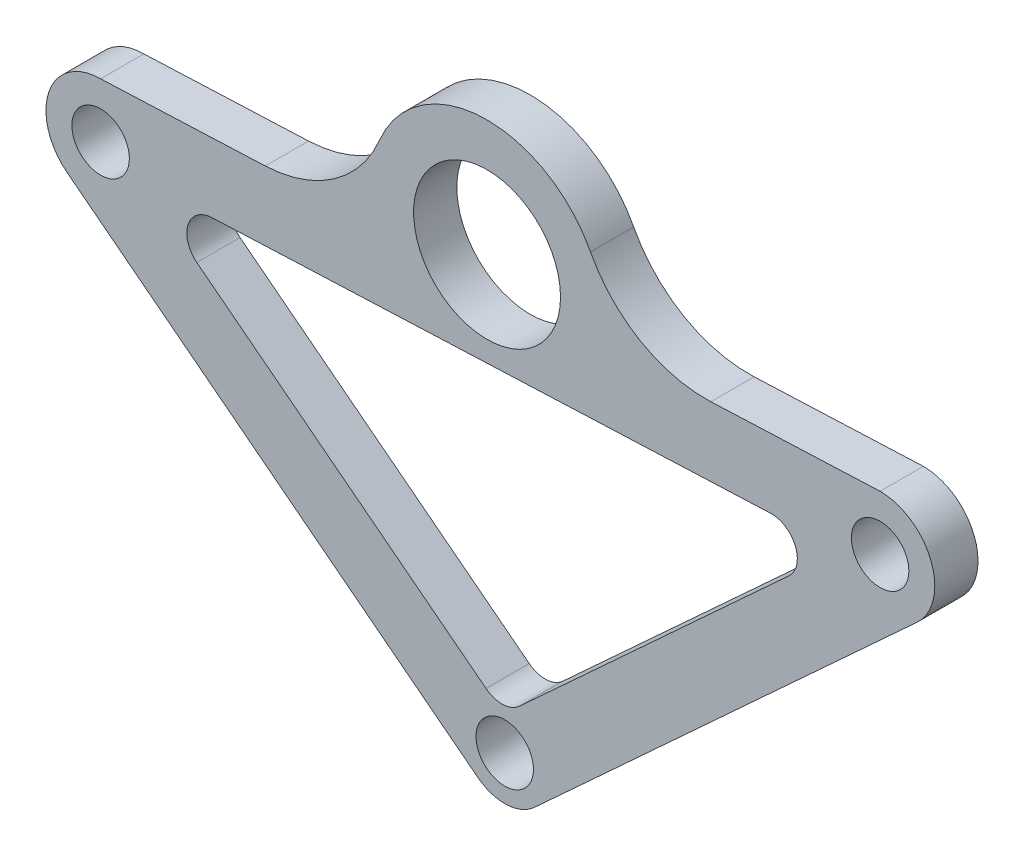
SolidWorks part; units mm, degrees
ref_plane "Front Plane" through (0, 0, 0) normal (0, 0, 1) x (1, 0, 0)
ref_plane "Top Plane" through (0, 0, 0) normal (0, 1, 0) x (1, 0, 0)
ref_plane "Right Plane" through (0, 0, 0) normal (1, 0, 0) x (0, 0, -1)
sketch "Sketch1" plane through (0, 0, 0) normal (0, 0, 1) x (1, 0, 0)
  line L0 (57.5247, 15.0168) -> (37.9425, 14.1987)
  line L1 (44.8204, 6.4791) -> (-19.8121, 3.7789)
  line L2 (-21.5254, -1.5891) -> (11.9313, -27.5371)
  line L3 (15.7998, -27.3755) -> (46.9755, 1.2727)
  line L4 (-31.6301, 6.2478) -> (15.8829, -30.6018) construction
  line L5 (-36.5329, -0.0738) -> (10.9801, -36.9234)
  line L6 (17.5306, -36.6497) -> (61.8044, 4.0346)
  line L7 (60.6221, 14.2065) -> (26.9742, 33.1051)
  line L8 (26.9742, 33.1051) -> (-20.235, 31.1328)
  line L9 (-20.235, 31.1328) -> (-37.6439, 8.8143)
  line L10 (-36.5329, -0.0738) -> (10.9801, -36.9234)
  line L11 (17.5306, -36.6497) -> (61.8044, 4.0346)
  line L12 (57.8586, 7.0238) -> (-32.3227, 3.2562) construction
  line L13 (12.1176, -30.7591) -> (56.3913, 9.9252) construction
  line L15 (-13.602, 12.0453) -> (-32.6566, 11.2492)
  line L16 (57.5247, 15.0168) -> (-32.6566, 11.2492) construction
  circle A0 centre (-32.6566, 4.9242) radius 3.325 construction
  circle A1 centre (14.0933, -32.9092) radius 3.325 construction
  circle A2 centre (57.5247, 8.6918) radius 3.325 construction
  circle A3 centre (-32.6566, 4.9242) radius 3.325
  circle A4 centre (14.0933, -32.9092) radius 3.325
  circle A5 centre (57.5247, 8.6918) radius 3.325
  arc A6 (-32.6566, 11.2492) -> (-36.5329, -0.0738) centre (-32.6566, 4.9242) ccw
  arc A7 (61.8044, 4.0346) -> (56.9971, 14.9948) centre (57.5247, 8.6918) ccw
  arc A8 (11.9313, -27.5371) -> (15.7998, -27.3755) centre (13.7699, -25.1665) ccw
  arc A9 (-37.6439, 8.8143) -> (-36.5329, -0.0738) centre (-32.6566, 4.9242) ccw
  arc A10 (10.9801, -36.9234) -> (17.5306, -36.6497) centre (14.0933, -32.9092) ccw
  arc A11 (61.8044, 4.0346) -> (60.6221, 14.2065) centre (57.5247, 8.6918) ccw
  arc A13 (10.9801, -36.9234) -> (17.5306, -36.6497) centre (14.0933, -32.9092) ccw
  arc A14 (46.9755, 1.2727) -> (44.8204, 6.4791) centre (44.9456, 3.4817) ccw
  arc A15 (-21.5254, -1.5891) -> (-19.8121, 3.7789) centre (-19.6868, 0.7815) cw
  circle A16 centre (12.05, 16) radius 8.5 construction
  circle A17 centre (12.05, 16) radius 8.5
  arc A18 (24.0183, 22.2458) -> (-0.3975, 21.2258) centre (12.05, 16) ccw
  circle A19 centre (12.05, 16) radius 13.5 construction
  arc A20 (-13.602, 12.0453) -> (-0.3975, 21.2258) centre (-14.2281, 27.0322) ccw
  arc A21 (24.0183, 22.2458) -> (37.9425, 14.1987) centre (37.3164, 29.1856) ccw
  dimension "D3" = 3
  dimension "D5" = 15
  dimension "D6" = 15
  dimension "D1" = 0
  dimension "D2" = 8
  dimension "D4" = 5
extrude "Boss-Extrude1" add sketch "Sketch1" along normal mid plane 5 contours A21 A18 A20 L15 A6 L10 A13 L11 A7 L0 A17 A5 A4 A3 L2 A15 L1 A14 L3 A8
